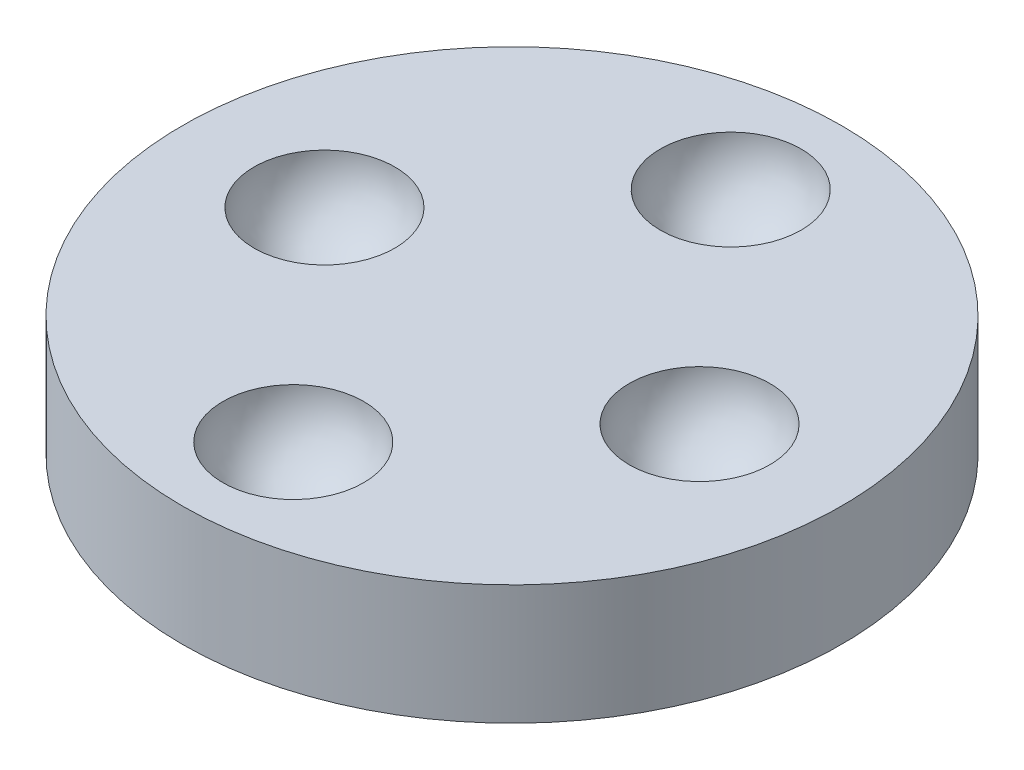
SolidWorks part; units mm, degrees
ref_plane "Front Plane" through (0, 0, 0) normal (0, 0, 1) x (1, 0, 0)
ref_plane "Top Plane" through (0, 0, 0) normal (0, 1, 0) x (1, 0, 0)
ref_plane "Right Plane" through (0, 0, 0) normal (1, 0, 0) x (0, 0, -1)
sketch "Sketch1" plane through (0, 0, 0) normal (0, 1, 0) x (1, 0, 0)
  circle A0 centre (0, 0) radius 13.97
  dimension "D1" = 27.94
extrude "Boss-Extrude1" add sketch "Sketch1" along normal blind 5.08
ref_plane "Plane1" through (0, 5.08, 0) normal (0, 1, 0) x (1, 0, 0)
sketch "Sketch2" plane through (0, 5.08, 0) normal (0, 1, 0) x (1, 0, 0)
  line L0 (0, 13.97) -> (0, -13.97) construction
  line L1 (-13.97, 0) -> (13.97, 0) construction
  line L2 (0, 0) -> (0, 9.271)
  circle A0 centre (0, 0) radius 13.97 construction
  dimension "D1" = 9.271
ref_plane "Plane3" through (0, 0, -9.271) normal (0, 0, 1) x (1, 0, 0)
sketch "Sketch3" plane through (0, 0, -9.271) normal (0, 0, 1) x (1, 0, 0)
  line L0 (-13.97, 5.08) -> (13.97, 5.08) construction
  line L3 (0, 5.08) -> (0, 2.0955)
  line L4 (2.9845, 5.08) -> (0, 5.08)
  arc A1 (0, 2.0955) -> (2.9845, 5.08) centre (0, 5.08) ccw
  dimension "D2" = 5.969
sketch "Sketch4" plane through (0, 5.08, 0) normal (0, 1, 0) x (1, 0, 0)
  line L0 (0, 0) -> (7.9502, 0)
  dimension "D1" = 7.9502
ref_plane "Plane4" through (7.9502, 0, 0) normal (1, 0, 0) x (0, 0, -1)
sketch "Sketch5" plane through (7.9502, 0, 0) normal (1, 0, 0) x (0, 0, -1)
  line L0 (13.97, 5.08) -> (-13.97, 5.08) construction
  line L3 (0, 5.08) -> (0, 2.0955)
  line L4 (-2.9845, 5.08) -> (0, 5.08)
  arc A1 (-2.9845, 5.08) -> (0, 2.0955) centre (0, 5.08) ccw
  dimension "D1" = 5.969
revolve "Cut-Revolve3" cut sketch "Sketch5" angle 360 about L3
mirror "Mirror3" about plane through (0, 0, 0) normal (1, 0, 0) of "Cut-Revolve3"
revolve "Cut-Revolve4" cut sketch "Sketch3" angle 360 about L3
mirror "Mirror4" about plane through (0, 0, 0) normal (0, 0, 1) of "Cut-Revolve4"
